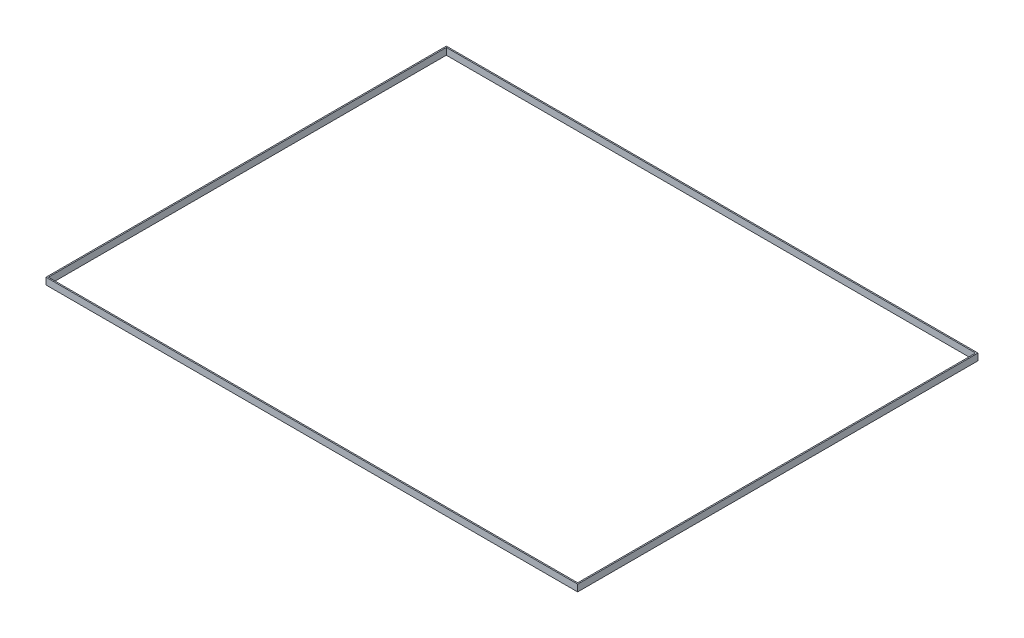
SolidWorks part; units mm, degrees
ref_plane "Front Plane" through (0, 0, 0) normal (0, 0, 1) x (1, 0, 0)
ref_plane "Top Plane" through (0, 0, 0) normal (0, 1, 0) x (1, 0, 0)
ref_plane "Right Plane" through (0, 0, 0) normal (1, 0, 0) x (0, 0, -1)
sketch "Sketch1" plane through (0, 0, 0) normal (0, 1, 0) x (1, 0, 0)
  line L0 (-6680, 5030) -> (6680, 5030)
  line L1 (-6650, -5000) -> (6650, -5000)
  line L2 (-6650, -5000) -> (-6650, 5000)
  line L3 (-6650, 5000) -> (6650, 5000)
  line L4 (6650, -5000) -> (6650, 5000)
  line L5 (-6650, -5000) -> (6650, 5000) construction
  line L6 (-6650, 5000) -> (6650, -5000) construction
  line L7 (6680, -5030) -> (6680, 5030)
  line L8 (-6680, -5030) -> (6680, -5030)
  line L9 (-6680, -5030) -> (-6680, 5030)
  point P0 (0, 0)
  dimension "D1" = 13300
  dimension "D2" = 10000
  dimension "D3" = 30
extrude "Boss-Extrude1" add sketch "Sketch1" along normal blind 170
